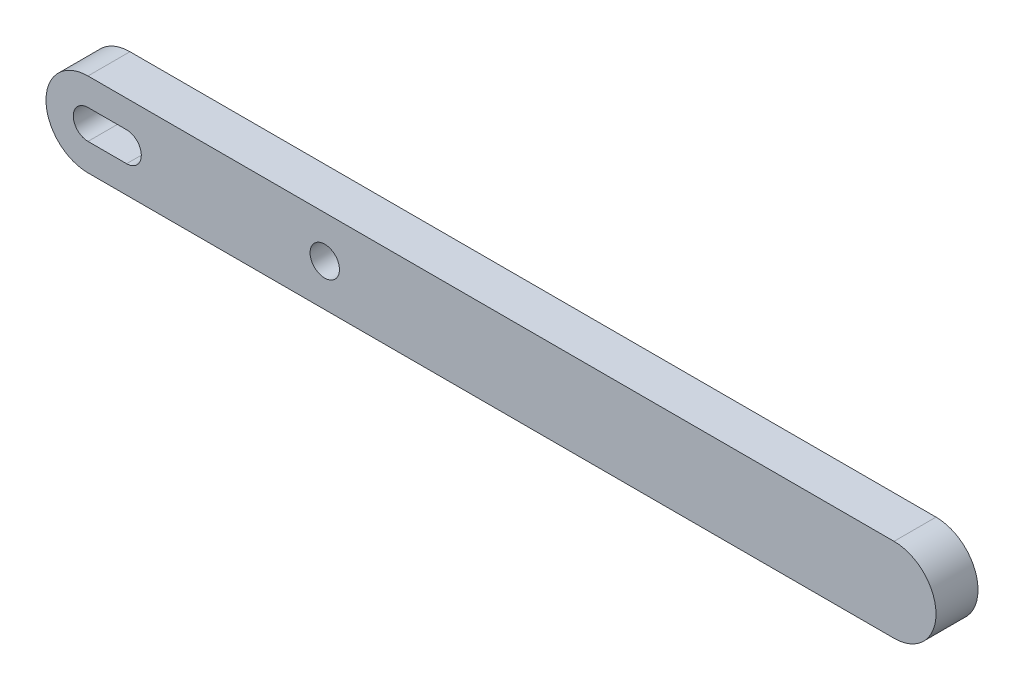
SolidWorks part; units mm, degrees
ref_plane "Front Plane" through (0, 0, 0) normal (1, 0, 0) x (0, 1, 0)
ref_plane "Top Plane" through (0, 0, 0) normal (0, 0, 1) x (0, 1, 0)
ref_plane "Right Plane" through (0, 0, 0) normal (0, 1, 0) x (-1, 0, 0)
sketch "Sketch1" plane through (0, 0, 0) normal (0, 0, 1) x (0, 1, 0)
  line L0 (0, 0) -> (0, 96) construction
  line L1 (-5, 0) -> (-5, 96)
  line L2 (5, 0) -> (5, 96)
  line L3 (0, 96) -> (0, 91.4) construction
  line L4 (1.75, 96) -> (1.75, 91.4)
  line L5 (-1.75, 96) -> (-1.75, 91.4)
  arc A0 (-5, 0) -> (5, 0) centre (0, 0) ccw
  arc A1 (5, 96) -> (-5, 96) centre (0, 96) ccw
  arc A2 (1.75, 96) -> (-1.75, 96) centre (0, 96) ccw
  arc A3 (-1.75, 91.4) -> (1.75, 91.4) centre (0, 91.4) ccw
  circle A4 centre (0, 67.8) radius 1.75
  point P3 (0, 48)
  point P8 (0, 101)
  point P9 (0, -5)
  point P12 (0, 93.7)
  dimension "D2" = 5
  dimension "D3" = 1.75
  dimension "D4" = 3.5
  dimension "D1" = 106
  dimension "D5" = 4.6
  dimension "D6" = 28.2
extrude "Boss-Extrude1" add sketch "Sketch1" along normal blind 5
